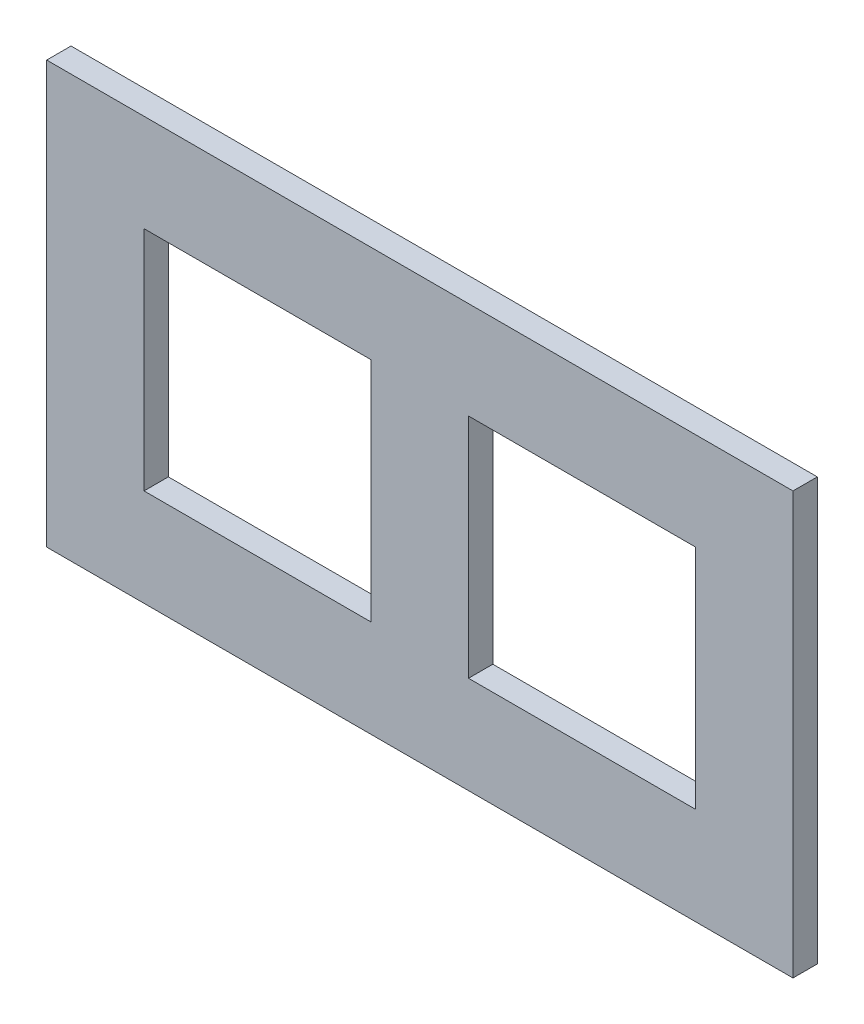
SolidWorks part; units mm, degrees
ref_plane "Front Plane" through (0, 0, 0) normal (0, 0, 1) x (1, 0, 0)
ref_plane "Top Plane" through (0, 0, 0) normal (0, 1, 0) x (1, 0, 0)
ref_plane "Right Plane" through (0, 0, 0) normal (1, 0, 0) x (0, 0, -1)
sketch "Sketch1" plane through (0, 0, 0) normal (0, 0, 1) x (1, 0, 0)
  line L1 (0, 0) -> (-46, 0)
  line L2 (0, 0) -> (0, 26)
  line L3 (0, 26) -> (-46, 26)
  line L4 (-46, 0) -> (-46, 26)
  line L5 (-40, 20) -> (-26, 20)
  line L6 (-40, 20) -> (-40, 6)
  line L7 (-40, 6) -> (-26, 6)
  line L8 (-26, 20) -> (-26, 6)
  line L9 (-20, 20) -> (-6, 20)
  line L10 (-20, 20) -> (-20, 6)
  line L11 (-20, 6) -> (-6, 6)
  line L12 (-6, 20) -> (-6, 6)
  dimension "D1" = 14
  dimension "D2" = 6
  dimension "D3" = 6
  dimension "D4" = 6
  dimension "D5" = 6
  dimension "D6" = 6
extrude "Boss-Extrude1" add sketch "Sketch1" along normal blind 1.5
